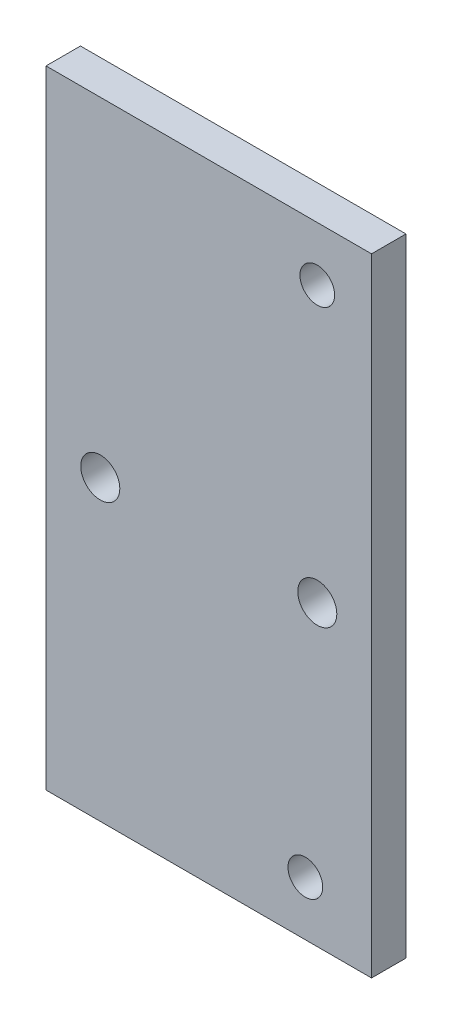
SolidWorks part; units mm, degrees
ref_plane "Front Plane" through (0, 0, 0) normal (0, 0, 1) x (1, 0, 0)
ref_plane "Top Plane" through (0, 0, 0) normal (0, 1, 0) x (1, 0, 0)
ref_plane "Right Plane" through (0, 0, 0) normal (1, 0, 0) x (0, 0, -1)
sketch "Sketch1" plane through (0, 0, 0) normal (0, 0, 1) x (1, 0, 0)
  line L1 (127.7364, 30.3482) -> (97.7364, 30.3482)
  line L2 (127.7364, 30.3482) -> (127.7364, -27.4518)
  line L3 (127.7364, -27.4518) -> (97.7364, -27.4518)
  line L4 (97.7364, 30.3482) -> (97.7364, -27.4518)
  circle A0 centre (121.6364, -22.4518) radius 1.6
  circle A1 centre (122.7364, 25.3482) radius 1.6
  circle A2 centre (102.7364, 0) radius 1.8
  circle A3 centre (122.7364, 0) radius 1.8
  dimension "D1" = 1.1
  dimension "D2" = 3.2
  dimension "D3" = 3.2
  dimension "D4" = 47.8
  dimension "D5" = 5
  dimension "D6" = 5
  dimension "D9" = 3.6
  dimension "D10" = 3.6
  dimension "D11" = 5
  dimension "D12" = 5
  dimension "D7" = 5
  dimension "D8" = 30
extrude "Boss-Extrude1" add sketch "Sketch1" along normal blind 3.175
